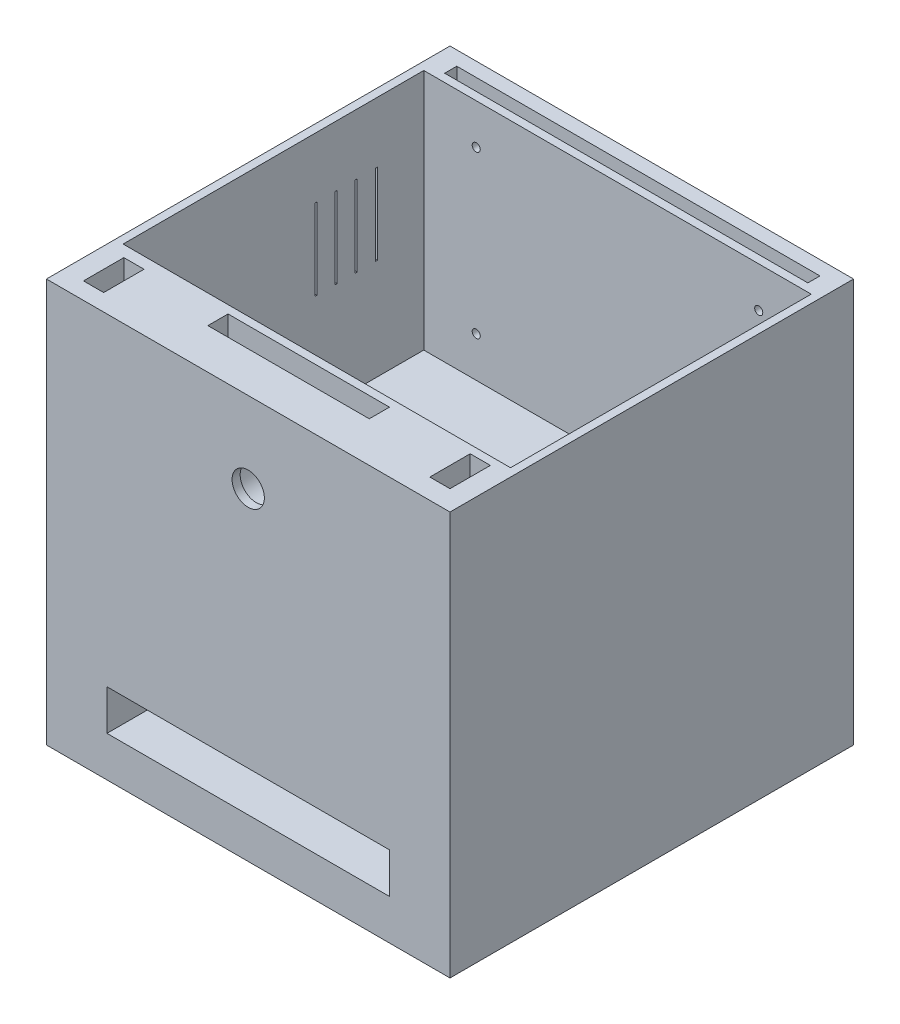
SolidWorks part; units mm, degrees
ref_plane "Front" through (0, 0, 0) normal (0, 0, 1) x (1, 0, 0)
ref_plane "Top" through (0, 0, 0) normal (0, 1, 0) x (1, 0, 0)
ref_plane "Right" through (0, 0, 0) normal (1, 0, 0) x (0, 0, -1)
sketch "Sketch1" plane through (0, 0, 0) normal (0, 0, 1) x (1, 0, 0)
  line L1 (0, 0) -> (100, 0)
  line L2 (0, 0) -> (0, -100)
  line L3 (0, -100) -> (100, -100)
  line L4 (100, 0) -> (100, -100)
  dimension "D1" = 100
  dimension "D2" = 100
extrude "Boss-Extrude1" add sketch "Sketch1" along normal blind 100
sketch "Sketch2" plane through (0, 0, 0) normal (0, 1, 0) x (1, 0, 0)
  line L0 (0, -100) -> (0, 0) construction
  line L1 (5, -10) -> (95, -10)
  line L2 (5, -10) -> (5, -80)
  line L3 (5, -80) -> (95, -80)
  line L4 (95, -10) -> (95, -80)
  line L5 (100, -100) -> (0, -100) construction
  dimension "D1" = 90
  dimension "D2" = 70
  dimension "D3" = 5
  dimension "D4" = 20
extrude "Cut-Extrude1" cut sketch "Sketch2" against normal blind 50
sketch "Sketch3" plane through (0, -50, 0) normal (0, 1, 0) x (1, 0, 0)
  line L0 (100, -100) -> (100, 0) construction
  line L1 (37.5, -67.5) -> (62.5, -67.5)
  line L2 (37.5, -67.5) -> (37.5, -42.5)
  line L3 (37.5, -42.5) -> (62.5, -42.5)
  line L4 (62.5, -67.5) -> (62.5, -42.5)
  line L5 (100, -100) -> (0, -100) construction
  dimension "D1" = 25
  dimension "D2" = 25
  dimension "D3" = 37.5
  dimension "D4" = 32.5
extrude "Cut-Extrude2" cut sketch "Sketch3" against normal blind 30
sketch "Sketch4" plane through (0, 0, 100) normal (0, 0, 1) x (1, 0, 0)
  line L0 (0, -100) -> (100, -100) construction
  line L1 (15, -80) -> (85, -80)
  line L2 (15, -80) -> (15, -90)
  line L3 (15, -90) -> (85, -90)
  line L4 (85, -80) -> (85, -90)
  line L5 (100, -100) -> (100, 0) construction
  dimension "D1" = 10
  dimension "D2" = 70
  dimension "D3" = 10
  dimension "D4" = 15
extrude "Cut-Extrude3" cut sketch "Sketch4" against normal blind 70
sketch "Sketch6" plane through (0, 0, 80) normal (0, 0, -1) x (-1, 0, 0)
  line L0 (-5, -50) -> (-5, 0) construction
  line L1 (-5, 0) -> (-95, 0) construction
  circle A0 centre (-50, -20) radius 5.5
  dimension "D1" = 45
  dimension "D2" = 20
sketch "Sketch7" plane through (0, 0, 100) normal (0, 0, 1) x (1, 0, 0)
  line L0 (100, 0) -> (0, 0) construction
  line L1 (0, 0) -> (0, -100) construction
  circle A0 centre (50, -20) radius 4
  dimension "D1" = 8
  dimension "D3" = 50
  dimension "D2" = 20
sketch "Sketch9" plane through (0, 0, 0) normal (-1, 0, 0) x (0, 0, 1)
  line L0 (100, 0) -> (0, 0) construction
  line L1 (20, -15) -> (20.5, -15)
  line L2 (20, -15) -> (20, -35)
  line L3 (20, -35) -> (20.5, -35)
  line L4 (20.5, -15) -> (20.5, -35)
  line L5 (0, 0) -> (0, -100) construction
  line L6 (25, -15) -> (25.5, -15)
  line L7 (25, -15) -> (25, -35)
  line L8 (25, -35) -> (25.5, -35)
  line L9 (25.5, -15) -> (25.5, -35)
  line L10 (30, -15) -> (30.5, -15)
  line L11 (30, -15) -> (30, -35)
  line L12 (30, -35) -> (30.5, -35)
  line L13 (30.5, -15) -> (30.5, -35)
  line L14 (35, -15) -> (35.5, -15)
  line L15 (35, -15) -> (35, -35)
  line L16 (35, -35) -> (35.5, -35)
  line L17 (35.5, -15) -> (35.5, -35)
  dimension "D1" = 20
  dimension "D2" = 0.5
  dimension "D3" = 15
  dimension "D4" = 20
  dimension "D5" = 25
  dimension "D6" = 15
  dimension "D7" = 20
  dimension "D8" = 30
  dimension "D9" = 15
  dimension "D10" = 20
  dimension "D11" = 35
  dimension "D12" = 15
  dimension "D13" = 20
extrude "Cut-Extrude7" cut sketch "Sketch9" against normal blind 10
sketch "Sketch15" plane through (0, 0, 0) normal (0, 1, 0) x (1, 0, 0)
  line L0 (0, -100) -> (0, 0) construction
  line L1 (70, -85) -> (30, -85)
  line L2 (70, -85) -> (70, -90)
  line L3 (70, -90) -> (30, -90)
  line L4 (30, -85) -> (30, -90)
  line L5 (100, -100) -> (0, -100) construction
  dimension "D1" = 40
  dimension "D2" = 30
  dimension "D3" = 10
  dimension "D4" = 5
extrude "Cut-Extrude8" cut sketch "Sketch15" against normal blind 5
sketch "Sketch16" plane through (0, 0, 0) normal (0, 1, 0) x (1, 0, 0)
  line L0 (0, -100) -> (0, 0) construction
  line L1 (5, -85.8181) -> (10, -85.8181)
  line L2 (5, -85.8181) -> (5, -95.8181)
  line L3 (5, -95.8181) -> (10, -95.8181)
  line L4 (10, -85.8181) -> (10, -95.8181)
  dimension "D1" = 10
  dimension "D2" = 5
  dimension "D3" = 5
extrude "Cut-Extrude9" cut sketch "Sketch16" against normal blind 5 contours L2 L1 L4 L3
sketch "Sketch17" plane through (0, 0, 0) normal (0, 1, 0) x (1, 0, 0)
  line L0 (100, -100) -> (100, 0) construction
  line L1 (90, -85) -> (95, -85)
  line L2 (90, -85) -> (90, -95)
  line L3 (90, -95) -> (95, -95)
  line L4 (95, -85) -> (95, -95)
  line L6 (5, -80) -> (95, -80) construction
  dimension "D1" = 10
  dimension "D2" = 5
  dimension "D3" = 5
  dimension "D4" = 5
extrude "Cut-Extrude10" cut sketch "Sketch17" against normal blind 5
sketch "Sketch18" plane through (0, 0, 30) normal (0, 0, 1) x (1, 0, 0)
sketch "Sketch19" plane through (0, 0, 30) normal (0, 0, 1) x (1, 0, 0)
sketch "Sketch20" plane through (0, 0, 30) normal (0, 0, 1) x (1, 0, 0)
  line L1 (15, -80) -> (85, -80)
  line L2 (15, -80) -> (15, -90)
  line L3 (15, -90) -> (85, -90)
  line L4 (85, -80) -> (85, -90)
extrude "Cut-Extrude11" cut sketch "Sketch20" against normal blind 20
sketch "Sketch21" plane through (0, 0, 0) normal (0, 1, 0) x (1, 0, 0)
  line L0 (95, -10) -> (5, -10) construction
  line L1 (5.1753, -3.5) -> (95.1753, -3.5)
  line L2 (5.1753, -3.5) -> (5.1753, -6.5)
  line L3 (5.1753, -6.5) -> (95.1753, -6.5)
  line L4 (95.1753, -3.5) -> (95.1753, -6.5)
  dimension "D1" = 90
  dimension "D2" = 3
  dimension "D3" = 3.5
extrude "Cut-Extrude12" cut sketch "Sketch21" against normal blind 5
sketch "Sketch22" plane through (0, 0, 10) normal (0, 0, 1) x (1, 0, 0)
  line L0 (5, -50) -> (5, 0) construction
  line L1 (95, 0) -> (5, 0) construction
  line L2 (95, -50) -> (95, 0) construction
  line L3 (95, -50) -> (5, -50) construction
  circle A0 centre (15, -10) radius 1
  circle A1 centre (85, -10) radius 1
  circle A2 centre (0, 0) radius 1
  circle A3 centre (85, -40) radius 1
  circle A4 centre (15, -50) radius 1
  dimension "D1" = 2
  dimension "D2" = 10
  dimension "D4" = 10
  dimension "D5" = 10
  dimension "D6" = 2
  dimension "D9" = 2
  dimension "D10" = 2
  dimension "D11" = 10
  dimension "D12" = 0
  dimension "D3" = 10
  dimension "D7" = 10
  dimension "D8" = 10
sketch "Sketch23" plane through (0, -50, 0) normal (0, 1, 0) x (1, 0, 0)
  line L1 (5, -10) -> (95, -10)
  line L2 (5, -10) -> (5, -80)
  line L3 (5, -80) -> (95, -80)
  line L4 (95, -10) -> (95, -80)
extrude "Cut-Extrude14" cut sketch "Sketch23" against normal blind 10
sketch "Sketch26" plane through (0, 0, 10) normal (0, 0, 1) x (1, 0, 0)
  line L0 (95, 0) -> (5, 0) construction
  line L1 (5, -60) -> (5, 0) construction
  line L2 (95, -60) -> (95, 0) construction
  line L3 (95, -60) -> (5, -60) construction
  circle A0 centre (15, -10) radius 1
  circle A1 centre (85, -10) radius 1
  circle A2 centre (85, -50) radius 1
  circle A3 centre (15, -50) radius 1
  dimension "D1" = 2
  dimension "D2" = 10
  dimension "D3" = 10
  dimension "D4" = 10
  dimension "D5" = 2
  dimension "D9" = 2
  dimension "D12" = 2
  dimension "D6" = 10
  dimension "D7" = 10
  dimension "D8" = 10
  dimension "D10" = 10
  dimension "D11" = 10
extrude "Cut-Extrude16" cut sketch "Sketch26" against normal blind 10
sketch "Sketch28" plane through (0, 0, 100) normal (0, 0, 1) x (1, 0, 0)
sketch "Sketch29" plane through (0, 0, 100) normal (0, 0, 1) x (1, 0, 0)
  line L0 (100, 0) -> (0, 0) construction
  line L1 (0, 0) -> (0, -100) construction
  circle A0 centre (50, -20) radius 4
  dimension "D1" = 8
  dimension "D2" = 20
  dimension "D3" = 50
extrude "Cut-Extrude20" cut sketch "Sketch29" against normal blind 11
sketch "Sketch30" plane through (0, 0, 100) normal (0, 0, 1) x (1, 0, 0)
  circle A0 centre (50, -20) radius 5.5
  dimension "D1" = 11
extrude "Cut-Extrude21" cut sketch "Sketch30" against normal blind 20 from offset 2 offset against normal yes
sketch "Sketch31" plane through (0, 0, 0) normal (0, 1, 0) x (1, 0, 0)
  line L0 (5.1753, -6.5) -> (95.1753, -6.5) construction
  line L1 (2, -8.5) -> (98, -8.5)
  line L2 (2, -8.5) -> (2, -83)
  line L3 (2, -83) -> (98, -83)
  line L4 (98, -8.5) -> (98, -83)
  line L5 (100, -100) -> (100, 0) construction
  line L6 (0, -100) -> (0, 0) construction
  line L7 (70, -85) -> (30, -85) construction
  dimension "D1" = 2
  dimension "D2" = 2
  dimension "D3" = 2
  dimension "D4" = 2
extrude "Cut-Extrude22" cut sketch "Sketch31" against normal blind 60 contours L2 L1 L4 L3
